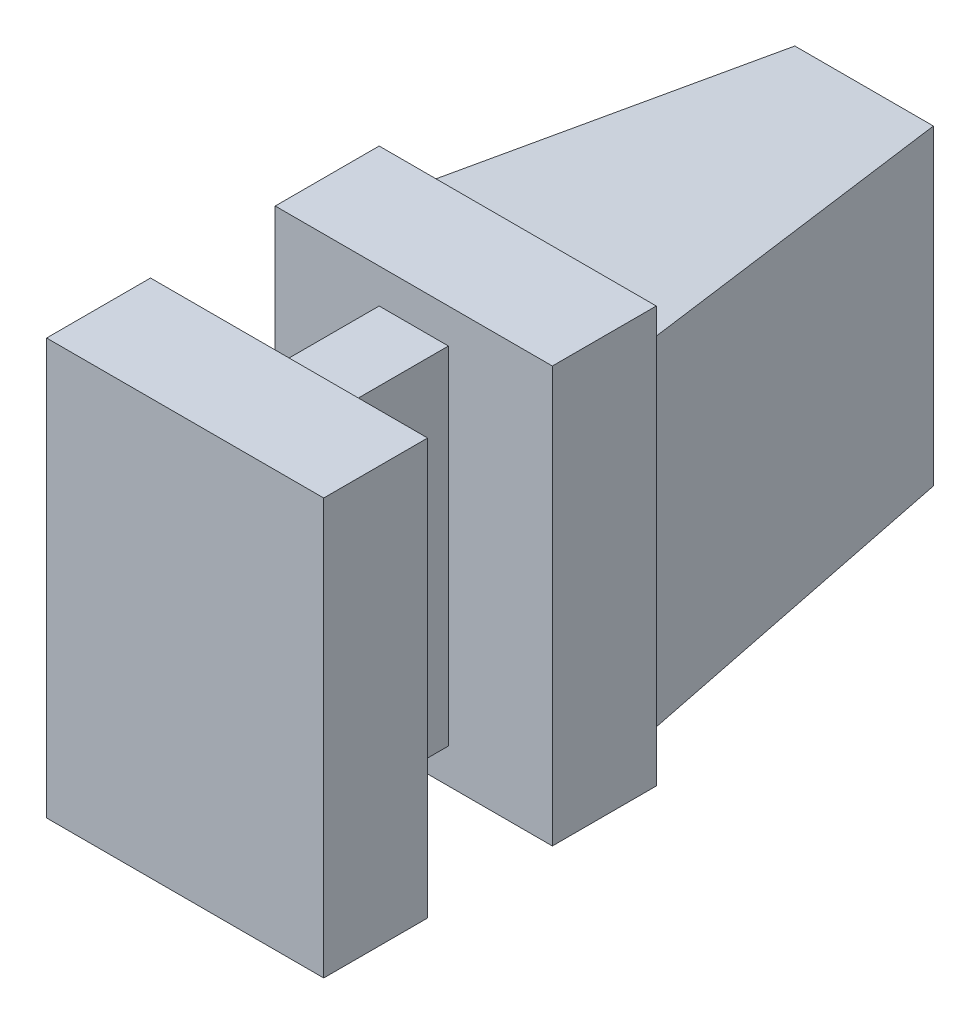
SolidWorks part; units mm, degrees
ref_plane "前基準面" through (0, 0, 0) normal (0, 0, 1) x (1, 0, 0)
ref_plane "上基準面" through (0, 0, 0) normal (0, 1, 0) x (1, 0, 0)
ref_plane "右基準面" through (0, 0, 0) normal (1, 0, 0) x (0, 0, -1)
sketch "草圖2" plane through (0, 0, 0) normal (0, 0, 1) x (1, 0, 0)
  line L1 (-0.5, 2.5) -> (0.5, 2.5)
  line L2 (-0.5, 2.5) -> (-0.5, -2.5)
  line L3 (-0.5, -2.5) -> (0.5, -2.5)
  line L4 (0.5, 2.5) -> (0.5, -2.5)
  line L5 (-0.5, 2.5) -> (0.5, -2.5) construction
  line L6 (-0.5, -2.5) -> (0.5, 2.5) construction
  point P0 (0, 0)
  dimension "D1" = 1
  dimension "D2" = 5
extrude "伸長1" add sketch "草圖2" along normal blind 1.8
sketch "草圖3" plane through (0, 0, 0) normal (0, 0, -1) x (-1, 0, 0)
  line L1 (-2, -3) -> (2, -3)
  line L2 (-2, -3) -> (-2, 3)
  line L3 (-2, 3) -> (2, 3)
  line L4 (2, -3) -> (2, 3)
  line L5 (-2, -3) -> (2, 3) construction
  line L6 (-2, 3) -> (2, -3) construction
  point P0 (0, 0)
  dimension "D1" = 6
  dimension "D2" = 4
extrude "伸長2" add sketch "草圖3" along normal blind 1.5
ref_plane "平面1" through (0, 0, 0.9) normal (0, 0, 1) x (1, 0, 0)
mirror "鏡射1" about plane through (0, 0, 0.9) normal (0, 0, 1) of "伸長2"
ref_plane "平面2" through (0, 0, -6.5) normal (0, 0, -1) x (-1, 0, 0)
sketch "草圖4" plane through (0, 0, -6.5) normal (0, 0, -1) x (-1, 0, 0)
  line L1 (-1, 2.25) -> (1, 2.25)
  line L2 (-1, 2.25) -> (-1, -2.25)
  line L3 (-1, -2.25) -> (1, -2.25)
  line L4 (1, 2.25) -> (1, -2.25)
  line L5 (-1, 2.25) -> (1, -2.25) construction
  line L6 (-1, -2.25) -> (1, 2.25) construction
  point P0 (0, 0)
  dimension "D1" = 4.5
  dimension "D2" = 2
sketch "草圖5" plane through (0, 0, -1.5) normal (0, 0, -1) x (-1, 0, 0)
  line L1 (-1.85, 2.45) -> (1.85, 2.45)
  line L2 (-1.85, 2.45) -> (-1.85, -2.45)
  line L3 (-1.85, -2.45) -> (1.85, -2.45)
  line L4 (1.85, 2.45) -> (1.85, -2.45)
  line L5 (-1.85, 2.45) -> (1.85, -2.45) construction
  line L6 (-1.85, -2.45) -> (1.85, 2.45) construction
  point P0 (0, 0)
  dimension "D1" = 3.7
  dimension "D2" = 4.9
loft "疊層拉伸1" add profiles "草圖4", "草圖5"
